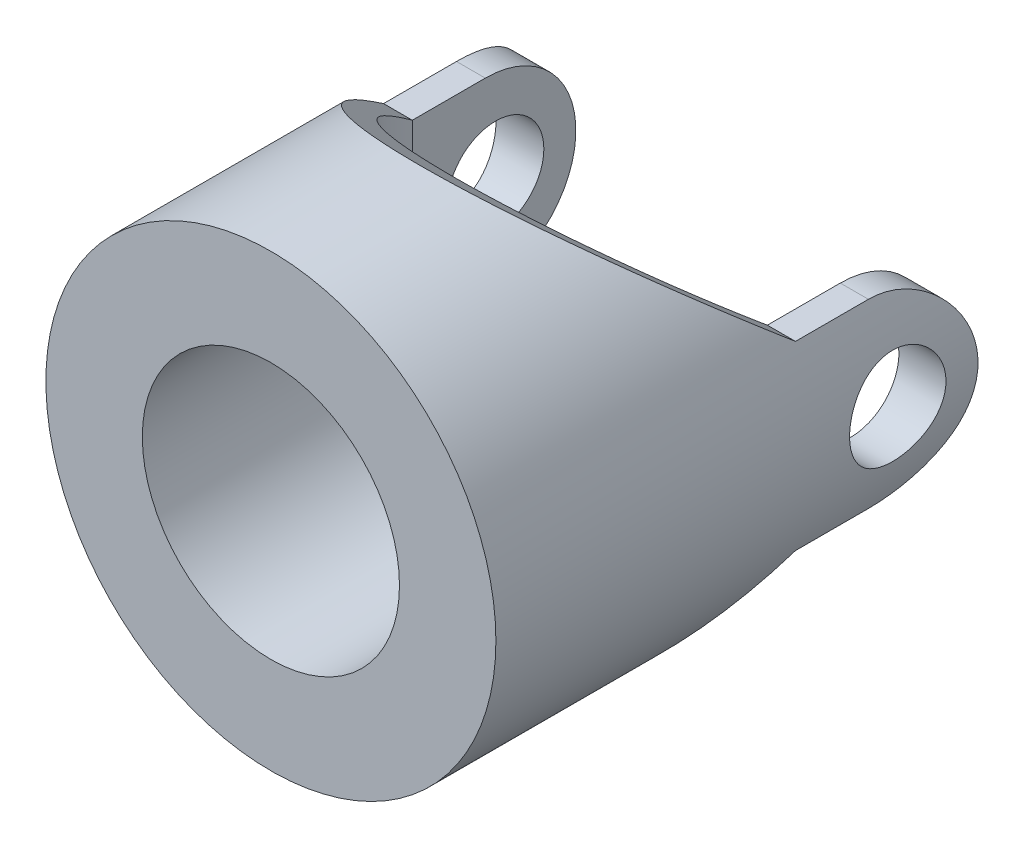
SolidWorks part; units mm, degrees
material "1060 Alloy"
ref_plane "Front Plane" through (0, 0, 0) normal (0, 0, 1) x (1, 0, 0)
ref_plane "Top Plane" through (0, 0, 0) normal (0, 1, 0) x (1, 0, 0)
ref_plane "Right Plane" through (0, 0, 0) normal (1, 0, 0) x (0, 0, -1)
sketch "Sketch1" plane through (0, 0, 0) normal (0, 0, 1) x (1, 0, 0)
  circle A0 centre (0, 0) radius 20
  circle A1 centre (0, 0) radius 35
  dimension "D1" = 40
  dimension "D2" = 70
extrude "Boss-Extrude1" add sketch "Sketch1" along normal blind 75
sketch "Sketch2" plane through (0, 0, 0) normal (1, 0, 0) x (0, 0, -1)
  line L0 (-14.0929, 14.0929) -> (-25.4393, 14.0929)
  line L1 (-14.0929, -14.0929) -> (-25.4393, -14.0929)
  line L2 (-25.4393, 14.0929) -> (-51.8435, 35)
  line L3 (-25.4393, -14.0929) -> (-52.1502, -35)
  line L4 (-51.8435, 35) -> (0, 35)
  line L5 (0, 35) -> (0, -35)
  line L6 (0, -35) -> (-52.1502, -35)
  line L7 (-75, -35) -> (0, -35) construction
  line L8 (0, 35) -> (-75, 35) construction
  arc A0 (-14.0929, -14.0929) -> (-14.0929, 14.0929) centre (-14.0929, 0) ccw
  point P10 (-52.1502, -35)
  point P14 (-51.8435, 35)
  point P17 (-52.0786, -34.9439)
extrude "Cut-Extrude1" cut sketch "Sketch2" against normal blind 54 and the other way blind 45 contours A0 L1 L3 L6 L5 | A0 L5 L4 L2 L0
sketch "Sketch3" plane through (0, 0, 0) normal (0, 1, 0) x (1, 0, 0)
  line L0 (-27.5588, 0) -> (-27.5588, -25.4393)
  line L5 (-32.0373, -25.4393) -> (-14.1912, -25.4393) construction
  line L7 (32.0373, -25.4393) -> (14.1912, -25.4393) construction
  line L8 (27.663, -25.4393) -> (27.663, 0)
  line L9 (35, 0) -> (20, 0) construction
  line L11 (-27.5588, 0) -> (27.663, 0)
  arc A1 (-27.5588, -25.4393) -> (27.663, -25.4393) centre (0.0521, -18.2148) ccw
extrude "Cut-Extrude2" cut sketch "Sketch3" against normal blind 44 and the other way blind 48
sketch "Sketch4" plane through (0, 0, 0) normal (1, 0, 0) x (0, 0, -1)
  circle A0 centre (-12.4833, 0) radius 7.5
  dimension "D1" = 15
extrude "Cut-Extrude3" cut sketch "Sketch4" against normal blind 44 and the other way blind 44
